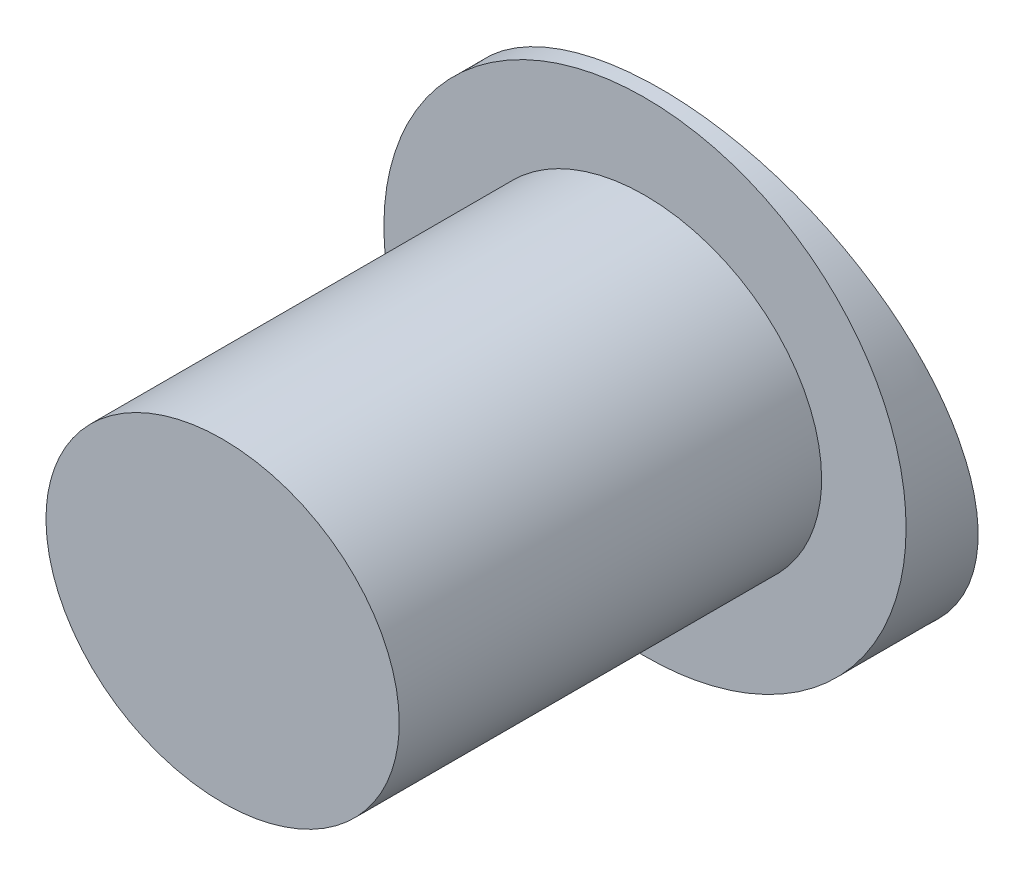
SolidWorks part; units mm, degrees
ref_plane "Plan de face" through (0, 0, 0) normal (0, 0, 1) x (1, 0, 0)
ref_plane "Plan de dessus" through (0, 0, 0) normal (0, 1, 0) x (1, 0, 0)
ref_plane "Plan de droite" through (0, 0, 0) normal (1, 0, 0) x (0, 0, -1)
sketch "Esquisse1" plane through (0, 0, 0) normal (0, 0, 1) x (1, 0, 0)
  ellipse E0 centre (0, 0) end of major axis (4.6, 0) minor radius 4.1
  dimension "D1" = 9.2
  dimension "D2" = 8.2
extrude "Boss.-Extru.1" add sketch "Esquisse1" against normal blind 11
sketch "Esquisse2" plane through (0, 0, -11) normal (0, 0, -1) x (-1, 0, 0)
  spline S0 degree 3 poles (6.8, -0.4333) (6.8, 0.4333) (6.7524, 0.8584) (6.5667, 1.6929) (6.4259, 2.1065) (6.065, 2.8835) (5.8451, 3.2502) (5.4572, 3.7682) (5.3185, 3.9347) (5.0279, 4.2501) (4.8753, 4.4) (4.5561, 4.6844) (4.3895, 4.819) (4.0421, 5.0729) (3.8609, 5.1925) (3.3068, 5.5218) (2.9208, 5.7049) (2.1166, 6.0013) (1.6961, 6.1143) (0.8538, 6.2629) (0.4284, 6.3001) (-0.2159, 6.3) (-0.4326, 6.2904) (-0.8608, 6.2526) (-1.0729, 6.2245) (-1.703, 6.1126) (-2.115, 6.0019) (-2.7205, 5.7787) (-2.9205, 5.6945) (-3.3078, 5.51) (-3.4962, 5.4094) (-4.0453, 5.0826) (-4.3903, 4.8317) (-4.8737, 4.4016) (-5.0282, 4.2498) (-5.3183, 3.9349) (-5.4548, 3.771) (-5.7104, 3.4304) (-5.8296, 3.2537) (-6.0502, 2.8869) (-6.152, 2.6957) (-6.4254, 2.1085) (-6.5632, 1.7043) (-6.7505, 0.8708) (-6.7994, 0.4361) (-6.8006, -0.4206) (-6.7546, -0.8455) (-6.6149, -1.4776) (-6.5565, -1.6867) (-6.4189, -2.0931) (-6.3395, -2.2917) (-6.16, -2.6799) (-6.0599, -2.8695) (-5.8388, -3.2396) (-5.7178, -3.42) (-5.3319, -3.9359) (-5.0422, -4.2506) (-4.5608, -4.6805) (-4.3918, -4.8171) (-4.0447, -5.0711) (-3.866, -5.1892) (-3.315, -5.5175) (-2.9262, -5.7027) (-2.116, -6.0017) (-1.7028, -6.1127) (-1.0715, -6.2247) (-0.8591, -6.2528) (-0.4305, -6.2906) (-0.2137, -6.3) (0.4308, -6.2999) (0.856, -6.2626) (1.6976, -6.1139) (2.1182, -6.0008) (2.9224, -5.7042) (3.3074, -5.5213) (4.0422, -5.0848) (4.3951, -4.8277) (5.0341, -4.2586) (5.3233, -3.9458) (5.7093, -3.4321) (5.8306, -3.2523) (6.0529, -2.8821) (6.1534, -2.6928) (6.4237, -2.112) (6.5625, -1.7081) (6.7519, -0.8645) (6.8, -0.4333) (6.8, 0.4333) (6.7524, 0.8584) knots -0.03125 -0.03125 0 0 0.03125 0.03125 0.0625 0.0625 0.09375 0.09375 0.109375 0.109375 0.125 0.125 0.140625 0.140625 0.15625 0.15625 0.1875 0.1875 0.21875 0.21875 0.25 0.25 0.265625 0.265625 0.28125 0.28125 0.3125 0.3125 0.328125 0.328125 0.34375 0.34375 0.375 0.375 0.390625 0.390625 0.40625 0.40625 0.421875 0.421875 0.4375 0.4375 0.46875 0.46875 0.5 0.5 0.53125 0.53125 0.546875 0.546875 0.5625 0.5625 0.578125 0.578125 0.59375 0.59375 0.625 0.625 0.640625 0.640625 0.65625 0.65625 0.6875 0.6875 0.71875 0.71875 0.734375 0.734375 0.75 0.75 0.78125 0.78125 0.8125 0.8125 0.84375 0.84375 0.875 0.875 0.90625 0.90625 0.921875 0.921875 0.9375 0.9375 0.96875 0.96875 1 1 1.03125 1.03125 1.0625 only from (6.8, 0) to (6.8, 0)
  spline S1 degree 3 poles (6.8, -0.4333) (6.8, 0.4333) (6.7524, 0.8584) (6.5667, 1.6929) (6.4259, 2.1065) (6.065, 2.8835) (5.8451, 3.2502) (5.4572, 3.7682) (5.3185, 3.9347) (5.0279, 4.2501) (4.8753, 4.4) (4.5561, 4.6844) (4.3895, 4.819) (4.0421, 5.0729) (3.8609, 5.1925) (3.3068, 5.5218) (2.9208, 5.7049) (2.1166, 6.0013) (1.6961, 6.1143) (0.8538, 6.2629) (0.4284, 6.3001) (-0.2159, 6.3) (-0.4326, 6.2904) (-0.8608, 6.2526) (-1.0729, 6.2245) (-1.703, 6.1126) (-2.115, 6.0019) (-2.7205, 5.7787) (-2.9205, 5.6945) (-3.3078, 5.51) (-3.4962, 5.4094) (-4.0453, 5.0826) (-4.3903, 4.8317) (-4.8737, 4.4016) (-5.0282, 4.2498) (-5.3183, 3.9349) (-5.4548, 3.771) (-5.7104, 3.4304) (-5.8296, 3.2537) (-6.0502, 2.8869) (-6.152, 2.6957) (-6.4254, 2.1085) (-6.5632, 1.7043) (-6.7505, 0.8708) (-6.7994, 0.4361) (-6.8006, -0.4206) (-6.7546, -0.8455) (-6.6149, -1.4776) (-6.5565, -1.6867) (-6.4189, -2.0931) (-6.3395, -2.2917) (-6.16, -2.6799) (-6.0599, -2.8695) (-5.8388, -3.2396) (-5.7178, -3.42) (-5.3319, -3.9359) (-5.0422, -4.2506) (-4.5608, -4.6805) (-4.3918, -4.8171) (-4.0447, -5.0711) (-3.866, -5.1892) (-3.315, -5.5175) (-2.9262, -5.7027) (-2.116, -6.0017) (-1.7028, -6.1127) (-1.0715, -6.2247) (-0.8591, -6.2528) (-0.4305, -6.2906) (-0.2137, -6.3) (0.4308, -6.2999) (0.856, -6.2626) (1.6976, -6.1139) (2.1182, -6.0008) (2.9224, -5.7042) (3.3074, -5.5213) (4.0422, -5.0848) (4.3951, -4.8277) (5.0341, -4.2586) (5.3233, -3.9458) (5.7093, -3.4321) (5.8306, -3.2523) (6.0529, -2.8821) (6.1534, -2.6928) (6.4237, -2.112) (6.5625, -1.7081) (6.7519, -0.8645) (6.8, -0.4333) (6.8, 0.4333) (6.7524, 0.8584) knots -0.03125 -0.03125 0 0 0.03125 0.03125 0.0625 0.0625 0.09375 0.09375 0.109375 0.109375 0.125 0.125 0.140625 0.140625 0.15625 0.15625 0.1875 0.1875 0.21875 0.21875 0.25 0.25 0.265625 0.265625 0.28125 0.28125 0.3125 0.3125 0.328125 0.328125 0.34375 0.34375 0.375 0.375 0.390625 0.390625 0.40625 0.40625 0.421875 0.421875 0.4375 0.4375 0.46875 0.46875 0.5 0.5 0.53125 0.53125 0.546875 0.546875 0.5625 0.5625 0.578125 0.578125 0.59375 0.59375 0.625 0.625 0.640625 0.640625 0.65625 0.65625 0.6875 0.6875 0.71875 0.71875 0.734375 0.734375 0.75 0.75 0.78125 0.78125 0.8125 0.8125 0.84375 0.84375 0.875 0.875 0.90625 0.90625 0.921875 0.921875 0.9375 0.9375 0.96875 0.96875 1 1 1.03125 1.03125 1.0625 only from (6.8, 0) to (6.8, 0)
  dimension "D1" = 2.2
extrude "Boss.-Extru.2" add sketch "Esquisse2" along normal blind 3
sketch "Esquisse3" plane through (0, 0, 0) normal (1, 0, 0) x (0, 0, -1)
  line L0 (14, 6.3) -> (11.4068, 6.3)
  line L1 (14, 6.3) -> (11, 6.3) construction
  line L2 (11.4068, 6.3) -> (14, -5.9)
  line L3 (14, -5.9) -> (14, 6.3)
  line L4 (14, -6.3) -> (14, 6.3) construction
  dimension "D1" = 12
extrude "Enlèv. mat.-Extru.1" cut sketch "Esquisse3" along normal through all both and the other way through all
